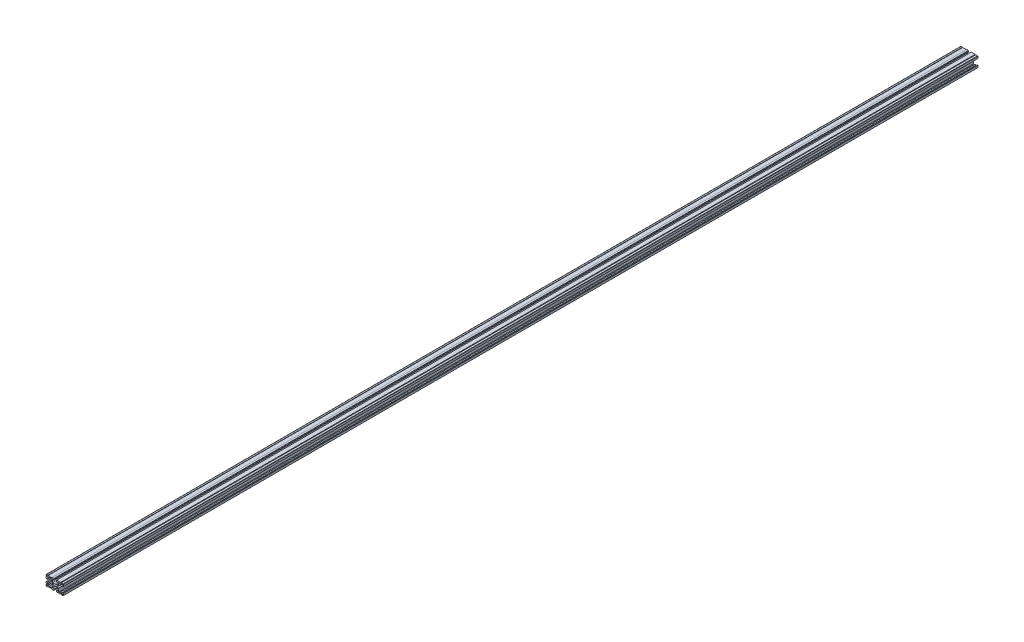
SolidWorks part; units mm, degrees
ref_plane "Front Plane" through (0, 0, 0) normal (0, 0, 1) x (1, 0, 0)
ref_plane "Top Plane" through (0, 0, 0) normal (0, 1, 0) x (1, 0, 0)
ref_plane "Right Plane" through (0, 0, 0) normal (1, 0, 0) x (0, 0, -1)
sketch "Sketch1" plane through (0, 0, 0) normal (0, 0, 1) x (1, 0, 0)
  line L0 (57.4896, 54.3357) -> (63.3602, 52.199)
  line L1 (73.5744, 54.3357) -> (67.7038, 52.199)
  line L2 (57.4896, 41.2953) -> (63.3602, 43.432)
  line L3 (73.5744, 41.2953) -> (67.7038, 43.432)
  line L4 (59.4868, 68.4911) -> (59.4868, 70.1675)
  line L5 (60.325, 68.4911) -> (59.4868, 68.4911)
  line L6 (71.5772, 68.4911) -> (70.739, 68.4911)
  line L7 (60.325, 64.1985) -> (60.325, 68.4911)
  line L8 (70.739, 64.1985) -> (70.739, 68.4911)
  line L9 (51.7144, 68.6435) -> (51.7144, 70.1675)
  line L10 (51.7144, 68.6435) -> (34.0868, 68.6435)
  line L11 (59.4868, 70.1675) -> (51.7144, 70.1675)
  line L12 (34.0868, 68.6435) -> (34.0868, 70.1675)
  line L13 (71.5772, 68.4911) -> (71.5772, 70.1675)
  line L14 (36.449, 58.8137) -> (36.449, 61.6585)
  line L15 (50.546, 52.2645) -> (50.546, 64.8335)
  line L16 (50.546, 64.8335) -> (39.624, 64.8335)
  line L17 (54.356, 58.8109) -> (54.356, 64.1985)
  line L18 (60.325, 64.1985) -> (54.356, 64.1985)
  line L19 (76.708, 58.8109) -> (76.708, 64.1985)
  line L20 (76.708, 64.1985) -> (70.739, 64.1985)
  line L21 (60.325, 31.4325) -> (54.356, 31.4325)
  line L22 (76.708, 31.4325) -> (70.739, 31.4325)
  line L23 (71.5772, 27.1399) -> (70.739, 27.1399)
  line L24 (60.325, 27.1399) -> (59.4868, 27.1399)
  line L25 (60.325, 27.1399) -> (60.325, 31.4325)
  line L26 (70.739, 27.1399) -> (70.739, 31.4325)
  line L27 (71.5772, 25.4635) -> (71.5772, 27.1399)
  line L28 (59.4868, 25.4635) -> (59.4868, 27.1399)
  line L29 (76.708, 31.4325) -> (76.708, 36.8201)
  line L30 (54.356, 31.4325) -> (54.356, 36.8201)
  line L31 (36.449, 58.8137) -> (31.369, 58.8137)
  line L32 (31.369, 52.832) -> (31.369, 58.8137)
  line L33 (25.4, 53.721) -> (27.051, 53.721)
  line L34 (27.051, 52.832) -> (31.369, 52.832)
  line L35 (27.051, 52.832) -> (27.051, 53.721)
  line L36 (27.305, 60.7822) -> (29.398, 62.8752)
  line L37 (51.7144, 26.9875) -> (34.0868, 26.9875)
  line L38 (34.0868, 26.9875) -> (34.0868, 25.4635)
  line L39 (36.449, 36.8173) -> (36.449, 33.9725)
  line L40 (36.449, 36.8173) -> (31.369, 36.8173)
  line L41 (31.369, 42.799) -> (31.369, 36.8173)
  line L42 (27.051, 42.799) -> (31.369, 42.799)
  line L43 (27.051, 42.799) -> (27.051, 41.91)
  line L44 (27.305, 34.8488) -> (29.398, 32.7558)
  line L45 (25.4, 41.91) -> (27.051, 41.91)
  line L46 (51.7144, 26.9875) -> (51.7144, 25.4635)
  line L47 (59.4868, 25.4635) -> (51.7144, 25.4635)
  line L48 (50.546, 30.7975) -> (39.624, 30.7975)
  line L49 (50.546, 30.7975) -> (50.546, 43.3665)
  line L50 (25.4, 60.7822) -> (27.305, 60.7822)
  line L51 (25.4, 53.721) -> (25.4, 60.7822)
  line L52 (25.4, 34.8488) -> (25.4, 41.91)
  line L53 (25.4, 34.8488) -> (27.305, 34.8488)
  line L54 (25.4, 65.3034) -> (25.4, 66.9925)
  line L55 (34.0868, 70.1675) -> (28.575, 70.1675)
  line L56 (27.305, 65.3034) -> (25.4, 65.3034)
  line L57 (28.0179, 66.5689) -> (27.305, 65.3034)
  line L58 (28.0179, 29.0621) -> (27.305, 30.3276)
  line L59 (27.305, 30.3276) -> (25.4, 30.3276)
  line L60 (25.4, 28.6385) -> (25.4, 30.3276)
  line L61 (34.0868, 25.4635) -> (28.575, 25.4635)
  line L62 (99.695, 68.8975) -> (99.695, 70.1675)
  line L63 (100.584, 68.8975) -> (99.695, 68.8975)
  line L64 (88.646, 67.5005) -> (88.646, 70.1675)
  line L65 (91.694, 67.5005) -> (91.694, 70.1675)
  line L66 (91.694, 67.5005) -> (88.646, 67.5005)
  line L67 (99.695, 70.1675) -> (91.694, 70.1675)
  line L68 (88.646, 70.1675) -> (71.5772, 70.1675)
  line L69 (80.518, 52.2645) -> (80.518, 65.9003)
  line L70 (98.679, 60.452) -> (97.8317, 64.2741)
  line L71 (92.964, 63.3349) -> (88.646, 63.3349)
  line L72 (82.2833, 65.9003) -> (80.518, 65.9003)
  line L73 (92.964, 63.3349) -> (92.964, 65.2907)
  line L74 (99.695, 26.7335) -> (99.695, 25.4635)
  line L75 (88.646, 28.1305) -> (88.646, 25.4635)
  line L76 (91.694, 28.1305) -> (91.694, 25.4635)
  line L77 (91.694, 28.1305) -> (88.646, 28.1305)
  line L78 (100.584, 35.179) -> (98.679, 35.179)
  line L79 (98.679, 35.179) -> (97.8317, 31.3569)
  line L80 (92.964, 32.2961) -> (88.646, 32.2961)
  line L81 (92.964, 32.2961) -> (92.964, 30.3403)
  line L82 (82.2833, 29.7307) -> (80.518, 29.7307)
  line L83 (80.518, 29.7307) -> (80.518, 43.3665)
  line L84 (88.646, 25.4635) -> (71.5772, 25.4635)
  line L85 (99.695, 25.4635) -> (91.694, 25.4635)
  line L87 (100.584, 26.7335) -> (100.584, 35.179)
  line L88 (100.584, 26.7335) -> (99.695, 26.7335)
  line L89 (100.584, 60.452) -> (100.584, 68.8975)
  line L90 (100.584, 60.452) -> (98.679, 60.452)
  arc A0 (50.546, 52.2645) -> (51.4195, 51.676) centre (51.181, 52.2645) ccw
  arc A1 (51.4195, 43.955) -> (51.4195, 51.676) centre (52.9844, 47.8155) ccw
  arc A2 (79.6445, 51.676) -> (79.6445, 43.955) centre (78.0796, 47.8155) ccw
  arc A3 (79.6445, 51.676) -> (80.518, 52.2645) centre (79.883, 52.2645) ccw
  arc A4 (54.356, 58.8109) -> (57.4896, 54.3357) centre (59.1185, 58.8109) ccw
  arc A5 (73.5744, 54.3357) -> (76.708, 58.8109) centre (71.9455, 58.8109) ccw
  arc A6 (63.3602, 52.199) -> (67.7038, 52.199) centre (65.532, 58.166) ccw
  arc A7 (67.7038, 43.432) -> (63.3602, 43.432) centre (65.532, 37.465) ccw
  arc A8 (39.624, 64.8335) -> (36.449, 61.6585) centre (39.624, 61.6585) ccw
  arc A9 (51.4195, 43.955) -> (50.546, 43.3665) centre (51.181, 43.3665) ccw
  arc A10 (80.518, 43.3665) -> (79.6445, 43.955) centre (79.883, 43.3665) ccw
  arc A11 (76.708, 36.8201) -> (73.5744, 41.2953) centre (71.9455, 36.8201) ccw
  arc A12 (57.4896, 41.2953) -> (54.356, 36.8201) centre (59.1185, 36.8201) ccw
  arc A13 (36.449, 33.9725) -> (39.624, 30.7975) centre (39.624, 33.9725) ccw
  arc A14 (28.575, 70.1675) -> (25.4, 66.9925) centre (28.575, 66.9925) ccw
  arc A15 (29.398, 62.8752) -> (28.0179, 66.5689) centre (30.2641, 65.3034) ccw
  arc A16 (28.0179, 29.0621) -> (29.398, 32.7558) centre (30.2641, 30.3276) ccw
  arc A17 (25.4, 28.6385) -> (28.575, 25.4635) centre (28.575, 28.6385) ccw
  arc A18 (97.8317, 64.2741) -> (92.964, 65.2907) centre (95.504, 65.2907) ccw
  arc A19 (84.9688, 65.0709) -> (88.646, 63.3349) centre (88.646, 68.0974) ccw
  arc A20 (84.9688, 65.0709) -> (82.2833, 65.9003) centre (82.2833, 61.1378) ccw
  arc A21 (92.964, 30.3403) -> (97.8317, 31.3569) centre (95.504, 30.3403) ccw
  arc A22 (88.646, 32.2961) -> (84.9688, 30.5601) centre (88.646, 27.5336) ccw
  arc A23 (82.2833, 29.7307) -> (84.9688, 30.5601) centre (82.2833, 34.4932) ccw
extrude "Extrude1" add sketch "Sketch1" along normal blind 3962.4
